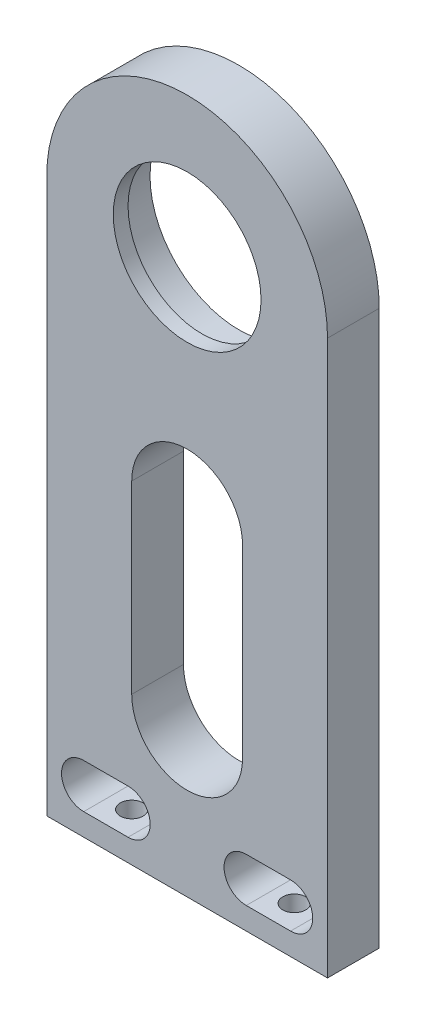
SolidWorks part; units mm, degrees
material "6061 合金"
ref_plane "前视基准面" through (0, 0, 0) normal (0, 0, 1) x (1, 0, 0)
ref_plane "上视基准面" through (0, 0, 0) normal (0, 1, 0) x (1, 0, 0)
ref_plane "右视基准面" through (0, 0, 0) normal (1, 0, 0) x (0, 0, -1)
sketch "草图1" plane through (0, 0, 0) normal (0, 0, 1) x (1, 0, 0)
  line L0 (0, 0) -> (0, 75) construction
  line L1 (-19, 0) -> (19, 0)
  line L2 (19, 0) -> (19, 7)
  line L3 (0, 45) -> (0, 20) construction
  line L4 (-19, 7) -> (-19, 0)
  line L5 (-19, 7) -> (-19, 75)
  line L6 (19, 7) -> (19, 75)
  line L7 (7.5, 45) -> (7.5, 20)
  line L8 (-7.5, 45) -> (-7.5, 20)
  line L9 (-8, 6) -> (-14, 6) construction
  line L10 (-8, 3) -> (-14, 3)
  line L11 (-8, 9) -> (-14, 9)
  line L12 (8, 6) -> (14, 6) construction
  line L13 (8, 3) -> (14, 3)
  line L14 (8, 9) -> (14, 9)
  circle A0 centre (0, 75) radius 10 construction
  circle A1 centre (0, 75) radius 19
  circle A2 centre (0, 75) radius 10
  arc A3 (-8, 3) -> (-8, 9) centre (-8, 6) ccw
  arc A4 (7.5, 45) -> (-7.5, 45) centre (0, 45) ccw
  arc A5 (-7.5, 20) -> (7.5, 20) centre (0, 20) ccw
  arc A6 (-14, 9) -> (-14, 3) centre (-14, 6) ccw
  arc A7 (8, 3) -> (8, 9) centre (8, 6) cw
  arc A8 (14, 9) -> (14, 3) centre (14, 6) cw
  point P16 (0, 32.5)
  point P21 (-11, 6)
  point P28 (11, 6)
  dimension "D1" = 20
  dimension "D3" = 75
  dimension "D4" = 30
  dimension "D5" = 7.5
  dimension "D6" = 20
  dimension "D10" = 6
  dimension "D7" = 8
  dimension "D8" = 6
  dimension "D9" = 3
  dimension "D2" = 38
extrude "凸台-拉伸1" add sketch "草图1" along normal blind 7
sketch "Sketch2" plane through (0, 0, 0) normal (0, 0, -1) x (-1, 0, 0)
  circle A0 centre (0, 75) radius 12.025
  dimension "D1" = 24.05
extrude "Cut-Extrude2" cut sketch "Sketch2" against normal blind 5
sketch "Sketch3" plane through (0, 0, 0) normal (0, -1, 0) x (1, 0, 0)
  line L0 (0, 0) -> (0, 24.3721) construction
  line L1 (19, 3.5) -> (-19, 3.5) construction
  line L2 (19, 7) -> (19, 0) construction
  line L3 (-19, 7) -> (-19, 0) construction
  circle A0 centre (11, 3.5) radius 1.55
  circle A1 centre (-11, 3.5) radius 1.55
  dimension "D1" = 3.1
  dimension "D2" = 8
extrude "Cut-Extrude3" cut sketch "Sketch3" against normal blind 5
sketch "Sketch5" [suppressed] plane through (0, 0, 0) normal (0, 0, -1) x (-1, 0, 0)
  line L0 (-19, 0) -> (-19, 75) construction
  line L1 (-19, 5) -> (19, 5)
  line L2 (-19, 5) -> (-19, 0)
  line L3 (-19, 0) -> (19, 0)
  line L4 (19, 5) -> (19, 0)
  line L5 (0, 0) -> (0, 114.7939) construction
  line L6 (19, 0) -> (19, 75) construction
  line L7 (16, 5) -> (12, 5)
  line L8 (16, 5) -> (16, 55)
  line L9 (16, 55) -> (12, 55)
  line L10 (12, 5) -> (12, 55)
  line L11 (-16, 5) -> (-16, 55)
  line L12 (-16, 55) -> (-12, 55)
  line L13 (-12, 5) -> (-12, 55)
  line L14 (-16, 5) -> (-12, 5)
  line M6 (-19, 75) -> (-19, 0)
  line M7 (-19, 0) -> (19, 0)
  line M8 (19, 0) -> (19, 75)
  dimension "D1" = 5
  dimension "D2" = 50
  dimension "D3" = 4
  dimension "D4" = 3
extrude "Boss-Extrude4" [suppressed] add sketch "Sketch5" along normal blind 10 contours L10 L1 L8 L9 | L5 L3 L1 M8 | L1 L13 L12 L11 | L5 L1 M7 M6
sketch "Sketch8" [suppressed] plane through (16, 0, 0) normal (1, 0, 0) x (0, 0, -1)
  line L0 (0, 55) -> (8, 5)
  line L1 (10, 5) -> (0, 5) construction
  line L5 (0, 55) -> (10, 55)
  line L6 (10, 55) -> (10, 5)
  line L7 (10, 5) -> (10, 55) construction
  line L8 (10, 5) -> (8, 5)
  dimension "D1" = 2
extrude "Cut-Extrude4" [suppressed] cut sketch "Sketch8" against normal through all
sketch "Sketch9" [suppressed] plane through (0, 0, 0) normal (0, -1, 0) x (-1, 0, 0)
  line L0 (0, 0) -> (0, 80.3898) construction
  line L1 (19, -7) -> (19, 10) construction
  line L2 (-19, 10) -> (19, 10) construction
  circle A0 centre (9, 5) radius 1.55
  circle A1 centre (-9, 5) radius 1.55
  dimension "D1" = 3.1
  dimension "D2" = 10
  dimension "D3" = 5
extrude "Cut-Extrude5" [suppressed] cut sketch "Sketch9" against normal blind 12
fillet "Fillet1" [suppressed] radius 2
fillet "Fillet2" [suppressed] radius 5
fillet "Fillet3" [suppressed] radius 2
fillet "Fillet4" [suppressed] radius 2
fillet "Fillet5" [suppressed] radius 2
